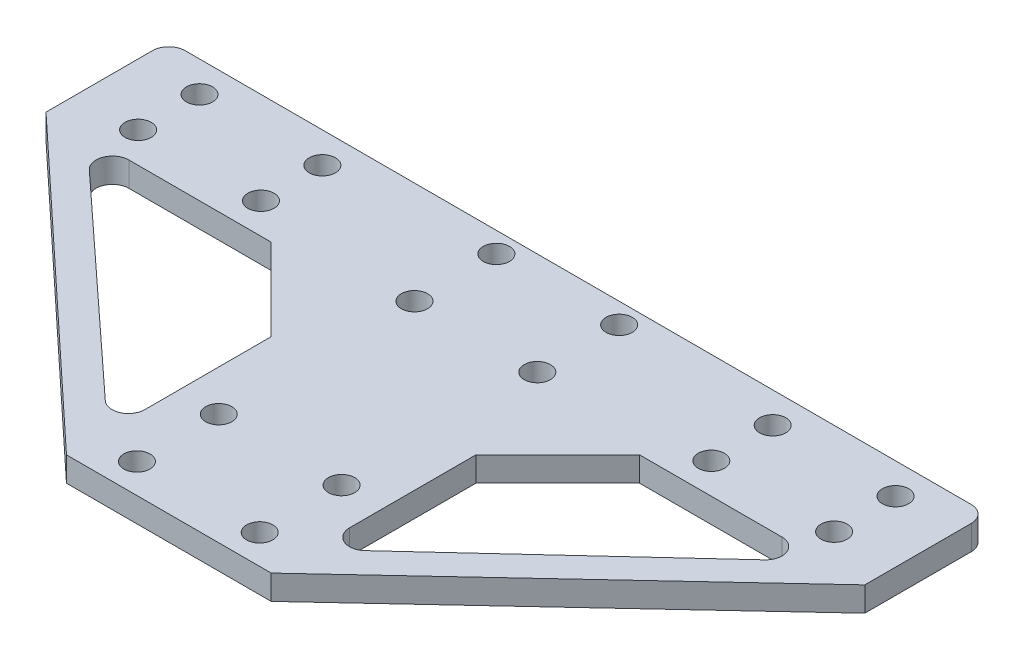
SolidWorks part; units mm, degrees
ref_plane "前视基准面" through (0, 0, 0) normal (0, 0, 1) x (1, 0, 0)
ref_plane "上视基准面" through (0, 0, 0) normal (0, 1, 0) x (1, 0, 0)
ref_plane "右视基准面" through (0, 0, 0) normal (1, 0, 0) x (0, 0, -1)
other "Configuration Table"
sketch "草图1" plane through (0, 0, 0) normal (0, 1, 0) x (1, 0, 0)
  line L1 (-50, -7.5) -> (50, -7.5)
  line L2 (-50, -7.5) -> (-50, 7.5)
  line L3 (-50, 7.5) -> (50, 7.5)
  line L4 (50, -7.5) -> (50, 7.5)
  line L5 (-50, -7.5) -> (50, 7.5) construction
  line L6 (-50, 7.5) -> (50, -7.5) construction
  point P0 (0, 0)
  dimension "D1" = 100
  dimension "D2" = 15
extrude "凸台-拉伸1" add sketch "草图1" along normal blind 3
sketch "草图2" plane through (0, 3, 0) normal (0, 1, 0) x (1, 0, 0)
  line L0 (50, 7.5) -> (-50, 7.5) construction
  line L1 (-12.5, 7.5) -> (12.5, 7.5)
  line L2 (-12.5, 7.5) -> (-12.5, -42.5)
  line L3 (-12.5, -42.5) -> (12.5, -42.5)
  line L4 (12.5, 7.5) -> (12.5, -42.5)
  line L5 (0, 0) -> (0, -13.2749) construction
  dimension "D1" = 25
  dimension "D2" = 50
extrude "凸台-拉伸2" add sketch "草图2" against normal blind 3
sketch "草图3" plane through (0, 3, 0) normal (0, 1, 0) x (1, 0, 0)
  line L0 (0, 7.5) -> (0, -8.6676) construction
  line L1 (50, 7.5) -> (-50, 7.5) construction
  line L2 (-50, 0) -> (0, 0) construction
  line L3 (-50, 7.5) -> (-50, -7.5) construction
  line L4 (-35, 7.5) -> (-35, -7.5) construction
  line L5 (-50, -7.5) -> (-12.5, -7.5) construction
  line L6 (-12.5, -42.5) -> (12.5, -42.5) construction
  circle A0 centre (-42.5, 3.75) radius 1.6
  circle A1 centre (-42.5, -3.75) radius 1.6
  circle A2 centre (-27.5, -3.75) radius 1.6
  circle A3 centre (-27.5, 3.75) radius 1.6
  circle A4 centre (27.5, -3.75) radius 1.6
  circle A5 centre (42.5, -3.75) radius 1.6
  circle A6 centre (42.5, 3.75) radius 1.6
  circle A7 centre (27.5, 3.75) radius 1.6
  circle A8 centre (-7.5, 5) radius 1.6
  circle A9 centre (-7.5, -5) radius 1.6
  circle A10 centre (7.5, -5) radius 1.6
  circle A11 centre (7.5, 5) radius 1.6
  circle A12 centre (-7.5, -28.9) radius 1.6
  circle A13 centre (-7.5, -38.9) radius 1.6
  circle A14 centre (7.5, -38.9) radius 1.6
  circle A15 centre (7.5, -28.9) radius 1.6
  dimension "D2" = 3.2
  dimension "D5" = 3.2
  dimension "D1" = 35
  dimension "D3" = 7.5
  dimension "D4" = 3.75
  dimension "D6" = 15
  dimension "D7" = 10
  dimension "D9" = 3.6
  dimension "D8" = 2
extrude "切除-拉伸1" cut sketch "草图3" against normal blind 3
sketch "草图4" plane through (0, 3, 0) normal (0, 1, 0) x (1, 0, 0)
  line L0 (-50, -7.5) -> (-12.5, -42.5)
  line L1 (-12.5, -42.5) -> (-12.5, -37.5)
  line L2 (-12.5, -7.5) -> (-12.5, -42.5) construction
  line L3 (-12.5, -37.5) -> (-45, -7.5)
  line L4 (-50, -7.5) -> (-12.5, -7.5) construction
  line L5 (-45, -7.5) -> (-50, -7.5)
  line L6 (0, 0) -> (0, -9.3553) construction
  line L7 (12.5, -37.5) -> (45, -7.5)
  line L8 (12.5, -42.5) -> (12.5, -37.5)
  line L9 (50, -7.5) -> (12.5, -42.5)
  line L10 (45, -7.5) -> (50, -7.5)
  dimension "D1" = 5
  dimension "D2" = 5
extrude "凸台-拉伸3" add sketch "草图4" against normal blind 3
chamfer "倒角1" distance 10 angle 45 2 edges at (12.5, 1.5, 7.5) (-12.5, 1.5, 7.5)
fillet "圆角2" radius 2 6 edges at (50, 1.5, -7.5) (-50, 1.5, -7.5) (45, 1.5, 7.5) (12.5, 1.5, 37.5) (-12.5, 1.5, 37.5) (-45, 1.5, 7.5)
